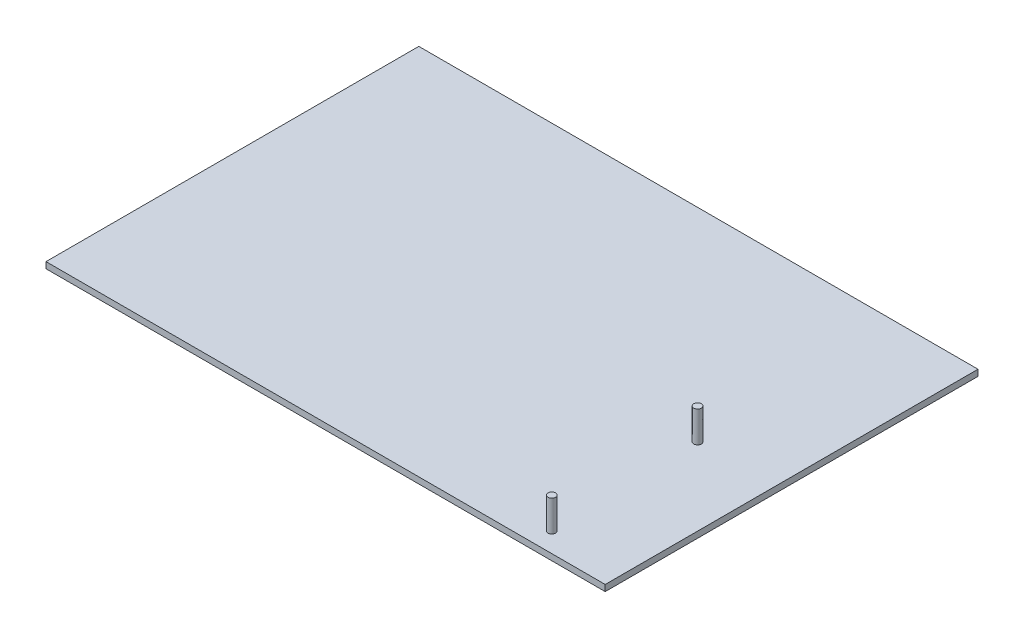
SolidWorks part; units mm, degrees
ref_plane "Ön Düzlem" through (0, 0, 0) normal (0, 0, 1) x (1, 0, 0)
ref_plane "Üst Düzlem" through (0, 0, 0) normal (0, 1, 0) x (1, 0, 0)
ref_plane "Sağ Düzlem" through (0, 0, 0) normal (1, 0, 0) x (0, 0, -1)
sketch "Çizim2" plane through (0, 0, 0) normal (0, 1, 0) x (1, 0, 0)
  line L1 (-90, -60) -> (90, -60)
  line L2 (-90, -60) -> (-90, 60)
  line L3 (-90, 60) -> (90, 60)
  line L4 (90, -60) -> (90, 60)
  line L5 (-90, -60) -> (90, 60) construction
  line L6 (-90, 60) -> (90, -60) construction
  point P0 (0, 0)
  dimension "D1" = 180
  dimension "D2" = 120
extrude "Yükseklik-Ekstrüzyon1" add sketch "Çizim2" along normal blind 2
sketch "Çizim3" plane through (0, 2, 0) normal (0, 1, 0) x (1, 0, 0)
  line L0 (66.5, -60) -> (66.5, -53.67) construction
  line L1 (-90, -60) -> (90, -60) construction
  line L2 (66.5, -53.67) -> (90, -53.67) construction
  line L3 (90, -60) -> (90, 60) construction
  line L4 (65.1, 60) -> (65.1, -5.37) construction
  line L5 (90, 60) -> (-90, 60) construction
  line L6 (65.1, -5.37) -> (90, -5.37) construction
  circle A0 centre (66.5, -53.67) radius 1.225
  circle A1 centre (65.1, -5.37) radius 1.225
  dimension "D3" = 2.45
  dimension "D6" = 2.45
  dimension "D1" = 23.5
  dimension "D2" = 6.33
  dimension "D4" = 65.37
  dimension "D5" = 24.9
extrude "Yükseklik-Ekstrüzyon2" add sketch "Çizim3" along normal blind 10
